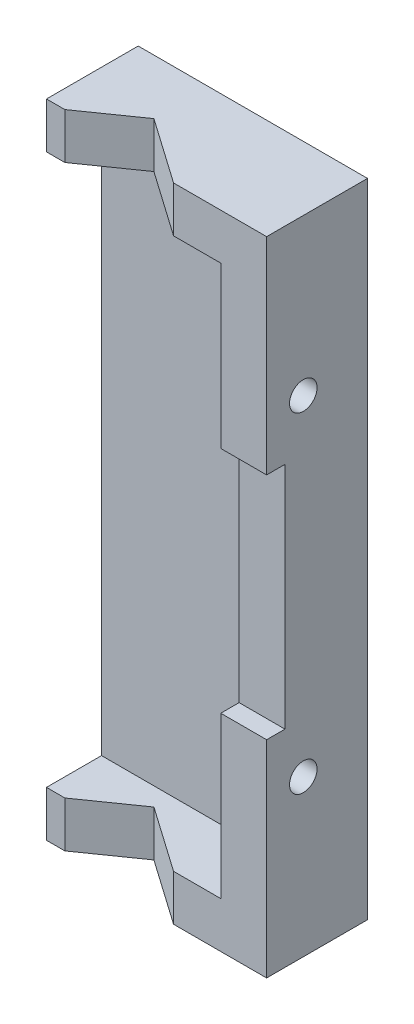
SolidWorks part; units mm, degrees
ref_plane "Front" through (0, 0, 0) normal (0, 0, 1) x (1, 0, 0)
ref_plane "Top" through (0, 0, 0) normal (0, 1, 0) x (1, 0, 0)
ref_plane "Right" through (0, 0, 0) normal (1, 0, 0) x (0, 0, -1)
sketch "Sketch1" plane through (0, 0, 0) normal (0, 0, 1) x (1, 0, 0)
  line L1 (-12.5, -35) -> (12.5, -35)
  line L2 (-12.5, -35) -> (-12.5, 35)
  line L3 (-12.5, 35) -> (12.5, 35)
  line L4 (12.5, -35) -> (12.5, 35)
  line L5 (-12.5, -35) -> (12.5, 35) construction
  line L6 (-12.5, 35) -> (12.5, -35) construction
  point P0 (0, 0)
  dimension "D1" = 70
  dimension "D2" = 25
extrude "Boss-Extrude1" add sketch "Sketch1" along normal blind 4
sketch "Sketch2" plane through (0, 35, 0) normal (0, 1, 0) x (1, 0, 0)
  line L0 (-4.7874, -6) -> (-10.5, -10)
  line L1 (-10.5, -10) -> (-12.5, -10)
  line L2 (-12.5, -4) -> (-12.5, -10)
  line L3 (-12.5, -4) -> (12.5, -4)
  line L4 (-4.7874, -6) -> (2.3533, -11)
  line L5 (2.3533, -11) -> (12.5, -11)
  line L6 (12.5, -4) -> (12.5, -11)
  line L7 (12.5, -4) -> (-12.5, -4) construction
  circle A0 centre (-4.7874, -12.1039) radius 5 construction
  dimension "D6" = 10
  dimension "D1" = 4
  dimension "D2" = 5
  dimension "D3" = 35
  dimension "D4" = 2
  dimension "D5" = 2
  dimension "D7" = 110
extrude "Boss-Extrude2" add sketch "Sketch2" against normal blind 5
sketch "Sketch3" plane through (0, -35, 0) normal (0, -1, 0) x (1, 0, 0)
  line L7 (2.3533, 11) -> (-4.7874, 6)
  line L8 (-4.7874, 6) -> (-10.5, 10)
  line L9 (-10.5, 10) -> (-12.5, 10)
  line L10 (-12.5, 10) -> (-12.5, 4)
  line L11 (-12.5, 4) -> (12.5, 4)
  line L12 (12.5, 4) -> (12.5, 11)
  line L13 (12.5, 11) -> (2.3533, 11)
  line L14 (2.3533, 11) -> (-4.7874, 6)
  line L15 (-4.7874, 6) -> (-10.5, 10)
  line L16 (-10.5, 10) -> (-12.5, 10)
  line L17 (-12.5, 10) -> (-12.5, 4)
  line L18 (-12.5, 4) -> (12.5, 4)
  line L19 (12.5, 4) -> (12.5, 11)
  line L20 (12.5, 11) -> (2.3533, 11)
  dimension "D1" = 0
extrude "Boss-Extrude3" add sketch "Sketch3" against normal blind 5
sketch "Sketch5" plane through (12.5, 0, 0) normal (1, 0, 0) x (0, 0, -1)
  line L6 (-11, 30) -> (-4, 30)
  line L7 (-11, 30) -> (-11, -30)
  line L8 (-11, -30) -> (-4, -30)
  line L9 (-4, 30) -> (-4, -30)
  line L10 (-11, 30) -> (-4, -30) construction
  line L11 (-11, -30) -> (-4, 30) construction
  circle A2 centre (-7, 18) radius 1.5
  circle A3 centre (-7, -18) radius 1.5
  point P4 (-7.5, 0)
  dimension "D3" = 18
  dimension "D4" = 18
  dimension "D1" = 3
  dimension "D2" = 3
  dimension "D5" = 3
  dimension "D6" = 3
extrude "Boss-Extrude4" add sketch "Sketch5" against normal blind 5
sketch "Sketch6" plane through (7.5, 0, 0) normal (-1, 0, 0) x (0, 0, 1)
  line L0 (11, 30) -> (11, -30) construction
  line L1 (11, 12.5) -> (9, 12.5)
  line L2 (11, 12.5) -> (11, -12.5)
  line L3 (11, -12.5) -> (9, -12.5)
  line L4 (9, 12.5) -> (9, -12.5)
  line L5 (11, 12.5) -> (9, -12.5) construction
  line L6 (11, -12.5) -> (9, 12.5) construction
  line L7 (4, 30) -> (11, 30) construction
  point P4 (10, 0)
  dimension "D1" = 25
  dimension "D2" = 2
  dimension "D3" = 17.5
extrude "Cut-Extrude1" cut sketch "Sketch6" against normal up to next
